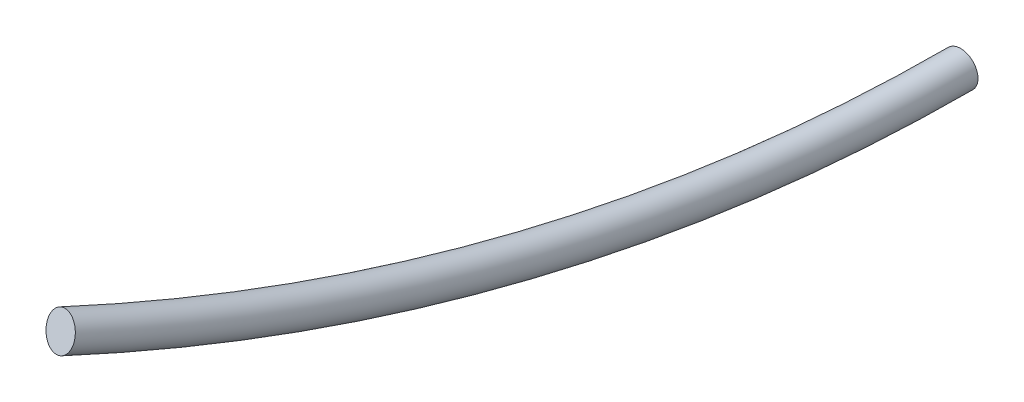
SolidWorks part; units mm, degrees
ref_plane "Front" through (0, 0, 0) normal (0, 0, 1) x (1, 0, 0)
ref_plane "Top" through (0, 0, 0) normal (0, 1, 0) x (1, 0, 0)
ref_plane "Right" through (0, 0, 0) normal (1, 0, 0) x (0, 0, -1)
sketch "Sketch1" plane through (0, 0, 0) normal (0, 0, 1) x (1, 0, 0)
  circle A0 centre (2774.8857, -12207.3502) radius 50.8
ref_plane "Plane1" through (-3668.0912, -2412.9539, 0) normal (-0.8354, -0.5496, 0) x (-0.2032, 0.3089, -0.9291)
sketch "Sketch2" plane through (-3668.0912, -2412.9539, 0) normal (-0.8354, -0.5496, 0) x (-0.2032, 0.3089, -0.9291)
  line L0 (-6369.9314, 9576.8218) -> (-7754.516, 8236.2129) construction
  line L1 (-4335.3382, 10892.5201) -> (-5836.9231, 10294.8734) construction
  arc A0 (-4335.3382, 10892.5201) -> (-6369.9314, 9576.8218) centre (-2026.0544, 5090.4536) ccw
  point P3 (-6212.2588, 9724.2921)
  point P5 (-5575.422, 10228.4256)
  point P6 (-4878.5402, 10645.6396)
  dimension "D1" = 2438.4
  dimension "D2" = 215.9
  dimension "D3" = 812.8
  dimension "D4" = 812.8
sweep "Sweep1" add profiles "Sketch1" path "Sketch2"
